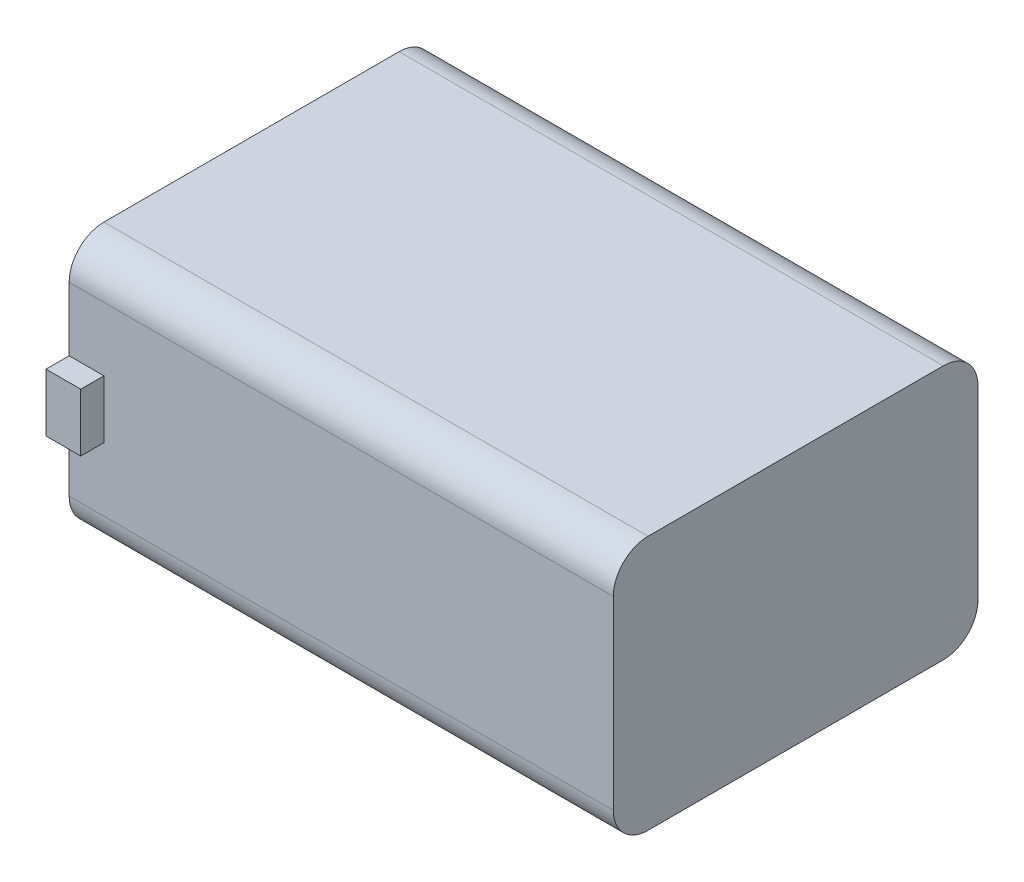
SolidWorks part; units mm, degrees
material "7075-T6 (SN)"
ref_plane "正面" through (0, 0, 0) normal (0, 0, 1) x (1, 0, 0)
ref_plane "平面" through (0, 0, 0) normal (0, 1, 0) x (1, 0, 0)
ref_plane "右側面" through (0, 0, 0) normal (1, 0, 0) x (0, 0, -1)
sketch "ｽｹｯﾁ1" plane through (0, 0, 0) normal (0, 1, 0) x (1, 0, 0)
  line L1 (-23.5, 15.75) -> (23.5, 15.75)
  line L2 (-23.5, 15.75) -> (-23.5, -15.75)
  line L3 (-23.5, -15.75) -> (23.5, -15.75)
  line L4 (23.5, 15.75) -> (23.5, -15.75)
  line L5 (-23.5, 15.75) -> (23.5, -15.75) construction
  line L6 (-23.5, -15.75) -> (23.5, 15.75) construction
  point P0 (0, 0)
  dimension "D1" = 47
  dimension "D2" = 31.5
extrude "ﾎﾞｽ - 押し出し1" add sketch "ｽｹｯﾁ1" along normal mid plane 22
fillet "ﾌｨﾚｯﾄ1" radius 3 4 edges at (0, -11, -15.75) (0, -11, 15.75) (0, 11, -15.75) (0, 11, 15.75)
sketch "ｽｹｯﾁ2" plane through (-23.5, 0, 0) normal (-1, 0, 0) x (0, 0, 1)
  line L0 (15.75, 8) -> (15.75, -8) construction
  line L1 (7.75, 2.5) -> (17.75, 2.5)
  line L2 (7.75, 2.5) -> (7.75, -2.5)
  line L3 (7.75, -2.5) -> (17.75, -2.5)
  line L4 (17.75, 2.5) -> (17.75, -2.5)
  line L5 (7.75, 2.5) -> (17.75, -2.5) construction
  line L6 (7.75, -2.5) -> (17.75, 2.5) construction
  point P4 (12.75, 0)
  dimension "D1" = 5
  dimension "D2" = 0
  dimension "D3" = 2
  dimension "D4" = 10
extrude "ﾎﾞｽ - 押し出し2" add sketch "ｽｹｯﾁ2" against normal blind 3
